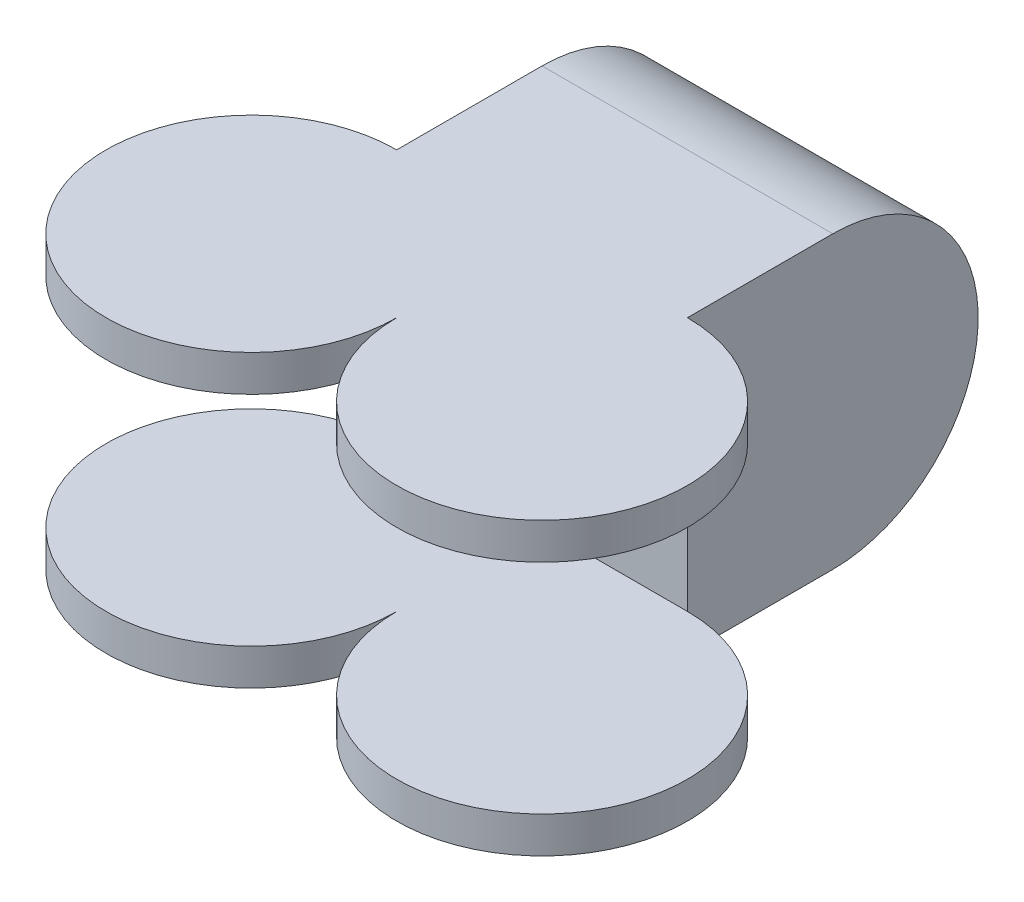
SolidWorks part; units mm, degrees
ref_plane "Front Plane" through (0, 0, 0) normal (0, 0, 1) x (1, 0, 0)
ref_plane "Top Plane" through (0, 0, 0) normal (0, 1, 0) x (1, 0, 0)
ref_plane "Right Plane" through (0, 0, 0) normal (1, 0, 0) x (0, 0, -1)
sketch "Sketch1" plane through (0, 0, 0) normal (1, 0, 0) x (0, 0, -1)
  line L1 (0, 40) -> (-80, 40)
  line L3 (0, -40) -> (-80, -40)
  line L4 (-80, 40) -> (-80, -40)
  arc A0 (0, -40) -> (0, 40) centre (0, 0) ccw
  dimension "D1" = 80
  dimension "D2" = 80
  dimension "D3" = 80
extrude "Boss-Extrude1" add sketch "Sketch1" along normal blind 80
sketch "Sketch2" plane through (0, 40, 0) normal (0, 1, 0) x (1, 0, 0)
  circle A0 centre (0, -80) radius 40
  circle A1 centre (80, -80) radius 40
  line M2 (0, 0) -> (0, -80)
  line M3 (0, -80) -> (80, -80)
  line M4 (80, -80) -> (80, 0)
  dimension "D1" = 80
extrude "Boss-Extrude2" add sketch "Sketch2" against normal blind 80 contours A0 M2 M3 | A1 M3 M4
sketch "Sketch3" plane through (80, 0, 0) normal (1, 0, 0) x (0, 0, -1)
  line L0 (-120, 40) -> (-120, -40) construction
  line L1 (-120, 30) -> (-40, 30)
  line L2 (-120, 30) -> (-120, -30)
  line L3 (-120, -30) -> (-40, -30)
  line L4 (-40, 30) -> (-40, -30)
  line L5 (-40, -40) -> (-40, 40) construction
  line L6 (-40, 40) -> (-120, 40) construction
  line L7 (-120, -40) -> (-40, -40) construction
  dimension "D1" = 10
  dimension "D2" = 10
extrude "Cut-Extrude1" cut sketch "Sketch3" against normal mid plane 266
